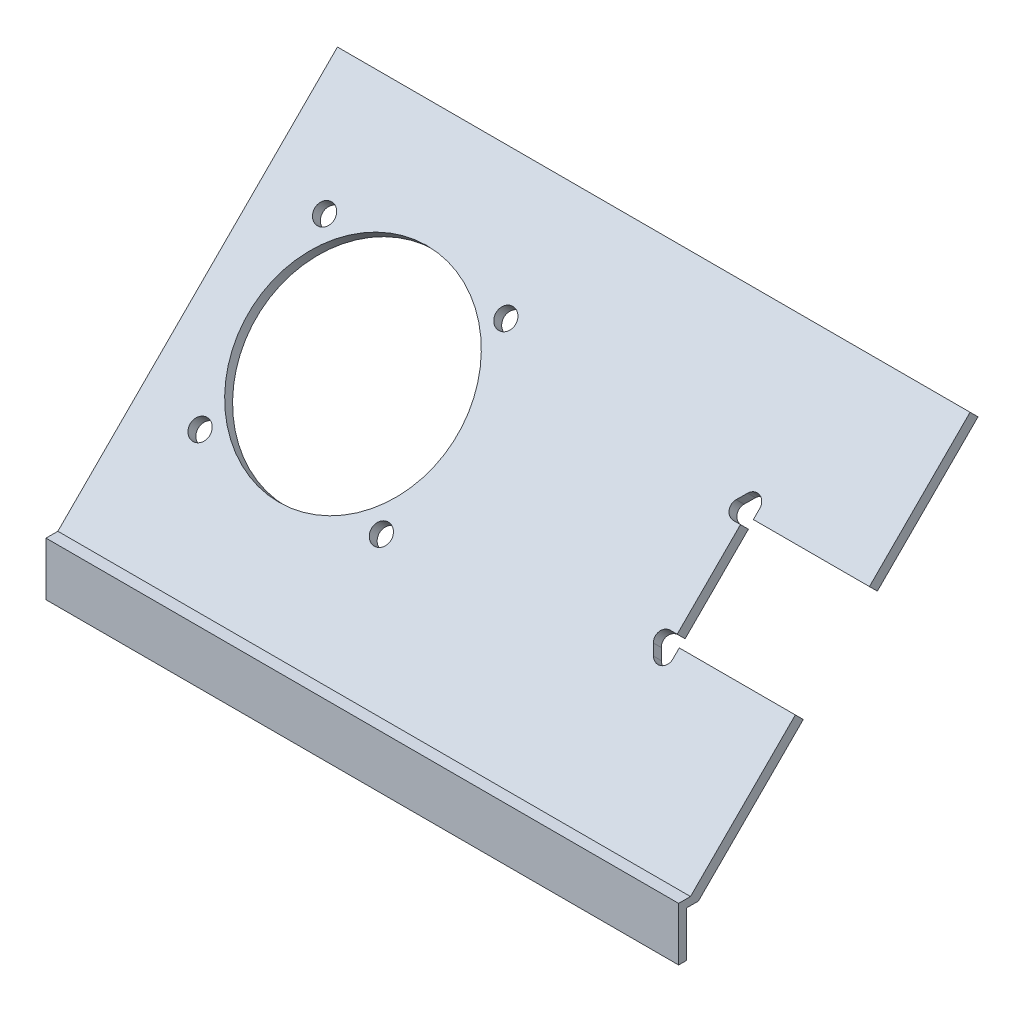
SolidWorks part; units mm, degrees
ref_plane "Front Plane" through (0, 0, 0) normal (0, 0, 1) x (1, 0, 0)
ref_plane "Top Plane" through (0, 0, 0) normal (0, 1, 0) x (1, 0, 0)
ref_plane "Right Plane" through (0, 0, 0) normal (1, 0, 0) x (0, 0, -1)
sketch "Sketch1" plane through (0, 0, 0) normal (1, 0, 0) x (0, 0, -1)
  line L0 (0, 0) -> (0, 11.5)
  line L1 (0, 11.5) -> (3, 11.5)
  line L2 (3, 11.5) -> (3, 13.5)
  line L3 (0, 0) -> (-2, 0)
  line L4 (3, 13.5) -> (-2, 13.5)
  line L5 (-2, 13.5) -> (-2, 0)
extrude "Boss-Extrude1" add sketch "Sketch1" along normal blind 160
sketch "Sketch2" plane through (0, 0, 0) normal (1, 0, 0) x (0, 0, -1)
  line L1 (3, 11.5) -> (24.2132, 32.7132)
  line L2 (1, 13.5) -> (71.7107, 84.2107)
  line L3 (3, 13.5) -> (1, 13.5)
  line L4 (3, 13.5) -> (-2, 13.5) construction
  line L5 (1, 13.5) -> (22.2132, 34.7132)
  line L7 (3, 13.5) -> (3, 11.5)
  line L9 (3, 11.5) -> (73.7107, 82.2107)
  line L10 (71.7107, 84.2107) -> (73.7107, 82.2107)
extrude "Boss-Extrude2" add sketch "Sketch2" along normal blind 160
sketch "Sketch3" plane through (0, 0, 2) normal (0, 0, 1) x (1, 0, 0)
  line L0 (0, 6.75) -> (10, 6.75)
  line L1 (0, 13.5) -> (0, 0) construction
  line L2 (160, 6.75) -> (152, 6.75)
  line L3 (160, 13.5) -> (160, 0) construction
sketch "Sketch4" plane through (0, 6.25, 6.25) normal (0, 0.7071, 0.7071) x (1, 0, 0)
  line L0 (160, 60.253) -> (128.75, 60.253)
  line L1 (160, 10.253) -> (160, 110.253) construction
  line L2 (128.75, 60.253) -> (128.75, 74.253)
  line L3 (160, 60.253) -> (160, 47.753)
  line L5 (128.75, 74.253) -> (160, 74.253)
  line L6 (128.75, 74.253) -> (128.75, 47.753)
  line L7 (128.75, 47.753) -> (160, 47.753)
  line L8 (160, 74.253) -> (160, 47.753)
  line M6 (160, 10.253) -> (160, 110.253)
extrude "Cut-Extrude1" cut sketch "Sketch4" against normal blind 10 contours L5 L2 L0 M6 | L6 L7 L0 M6
sketch "Sketch5" plane through (0, 6.25, 6.25) normal (0, 0.7071, 0.7071) x (1, 0, 0)
  line L0 (128.75, 74.253) -> (126.9822, 74.5208)
  line L1 (128.75, 61.003) -> (50.7631, 61.003)
  line L2 (128.75, 47.753) -> (128.75, 74.253) construction
  line L3 (126.9822, 74.5208) -> (128.4459, 76.5482) construction
  line L4 (125.2, 75.8075) -> (126.6636, 77.8349)
  line L5 (128.7645, 73.2342) -> (130.2281, 75.2615)
  line L6 (126.9822, 47.4853) -> (128.4459, 45.4579) construction
  line L9 (125.2, 46.1986) -> (126.6636, 44.1712)
  line L10 (130.6503, 76.5482) -> (126.9822, 76.5482)
  line L11 (130.644, 76.5482) -> (130.644, 72.3226)
  line L12 (130.644, 72.3226) -> (126.9822, 72.3226)
  line L13 (126.9822, 76.5482) -> (126.9822, 72.3226)
  line L14 (128.7645, 48.7719) -> (130.2281, 46.7445)
  line L15 (126.9822, 45.4579) -> (126.9822, 49.6834)
  line L16 (130.644, 49.6834) -> (126.9822, 49.6834)
  line L17 (130.644, 45.4579) -> (130.644, 49.6834)
  line L18 (130.6503, 45.4579) -> (126.9822, 45.4579)
  line L19 (128.75, 47.753) -> (126.9822, 47.4853)
  arc A2 (125.2, 75.8075) -> (128.7645, 73.2342) centre (126.9822, 74.5208) ccw
  arc A3 (130.2281, 75.2615) -> (126.6636, 77.8349) centre (128.4459, 76.5482) ccw
  arc A6 (125.2, 46.1986) -> (128.7645, 48.7719) centre (126.9822, 47.4853) cw
  arc A7 (130.2281, 46.7445) -> (126.6636, 44.1712) centre (128.4459, 45.4579) cw
  point P11 (127.714, 75.5345)
  point P16 (127.714, 46.4716)
  line M3 (128.75, 47.753) -> (128.75, 74.253)
  line M4 (128.75, 74.253) -> (160, 74.253)
  line M10 (160, 47.753) -> (128.75, 47.753)
extrude "Cut-Extrude2" cut sketch "Sketch5" against normal blind 10 contours A2 L12 L11 L5 M3 M4 | A2 L12 M3 | A3 L5 L11 M4 | A7 L18 L15 A6 L9 | A7 L14 L19 L15 L18 M10 | A6 L15 L19 M3 | A6 L14 L17 L16 M3 M10 | L16 A6 M3 | L14 A7 L17 M10
sketch "Sketch6" plane through (0, 6.25, 6.25) normal (0, 0.7071, 0.7071) x (1, 0, 0)
  line L0 (128.75, 61.003) -> (38.75, 61.003)
  line L1 (128.75, 49.6834) -> (128.75, 72.3226) construction
  line L3 (65.25, 34.503) -> (12.25, 34.503)
  line L4 (65.25, 34.503) -> (65.25, 87.503)
  line L5 (65.25, 87.503) -> (12.25, 87.503)
  line L6 (12.25, 34.503) -> (12.25, 87.503)
  line L7 (65.25, 34.503) -> (12.25, 87.503) construction
  line L8 (65.25, 87.503) -> (12.25, 34.503) construction
  circle A0 centre (38.75, 61.003) radius 26.5
extrude "Cut-Extrude3" cut sketch "Sketch6" against normal blind 10
sketch "Sketch7" plane through (0, 6.25, 6.25) normal (0, 0.7071, 0.7071) x (1, 0, 0)
  line L0 (38.75, 87.503) -> (38.75, 34.503)
  line L1 (12.24, 86.753) -> (15.8264, 83.2695)
  line L2 (12.24, 35.253) -> (65.26, 35.253)
  line L3 (12.24, 35.253) -> (12.24, 86.753)
  line L4 (12.24, 86.753) -> (65.26, 86.753)
  line L5 (65.26, 35.253) -> (65.26, 86.753)
  line L6 (12.24, 35.253) -> (65.26, 86.753) construction
  line L7 (12.24, 86.753) -> (65.26, 35.253) construction
  line L8 (12.24, 61.003) -> (65.26, 61.003)
  circle A0 centre (38.75, 61.003) radius 26.5 construction
  circle A1 centre (15.8264, 83.2695) radius 2.5
  circle A2 centre (15.8264, 38.7366) radius 2.5
  circle A3 centre (61.6736, 38.7366) radius 2.5
  circle A4 centre (61.6736, 83.2695) radius 2.5
  point P5 (38.75, 61.003)
extrude "Cut-Extrude4" cut sketch "Sketch7" against normal blind 10
ref_plane "Plane1" through (170, 0, 0) normal (1, 0, 0) x (0, 0, -1)
